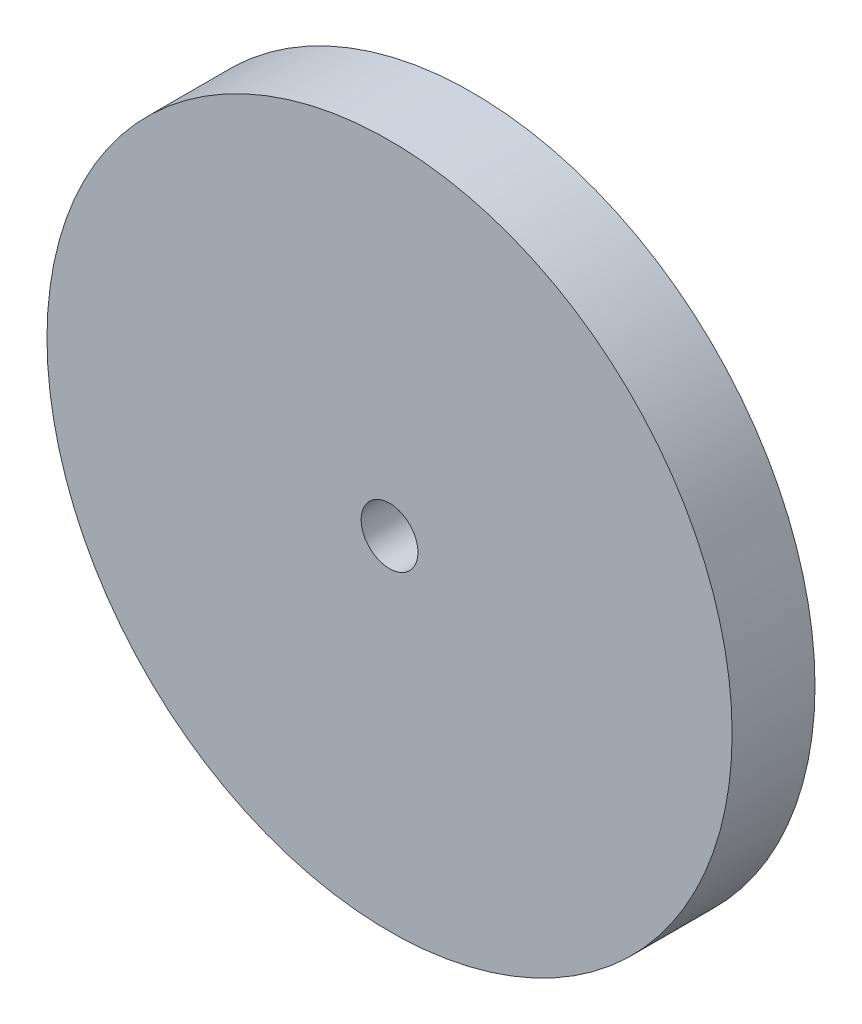
SolidWorks part; units mm, degrees
ref_plane "Front Plane" through (0, 0, 0) normal (0, 0, 1) x (1, 0, 0)
ref_plane "Top Plane" through (0, 0, 0) normal (0, 1, 0) x (1, 0, 0)
ref_plane "Right Plane" through (0, 0, 0) normal (1, 0, 0) x (0, 0, -1)
sketch "Sketch1" plane through (0, 0, 4.7625) normal (0, 0, 1) x (1, 0, 0)
  circle A1 centre (-41.4881, 0) radius 24.145
  circle A2 centre (-41.4881, 0) radius 2
  circle A3 centre (-41.4881, 0) radius 24.145 construction
  dimension "D1" = 4
extrude "Boss-Extrude1" add sketch "Sketch1" along normal blind 5.842
